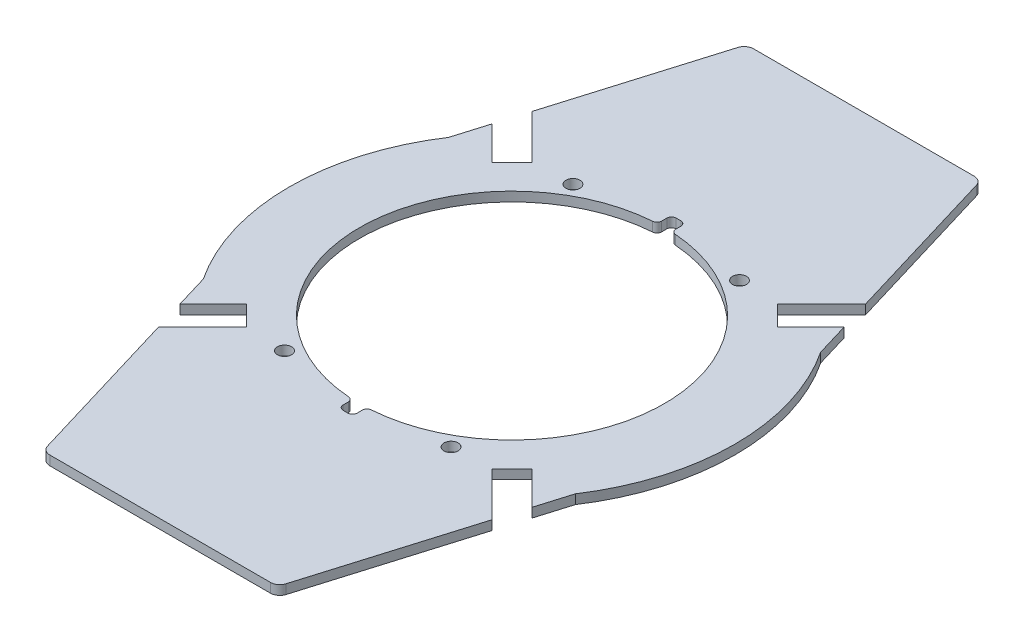
SolidWorks part; units mm, degrees
ref_plane "Front Plane" through (0, 0, 0) normal (0, 0, 1) x (1, 0, 0)
ref_plane "Top Plane" through (0, 0, 0) normal (0, 1, 0) x (1, 0, 0)
ref_plane "Right Plane" through (0, 0, 0) normal (1, 0, 0) x (0, 0, -1)
sketch "Sketch1" plane through (0, 0, 0) normal (0, 1, 0) x (1, 0, 0)
  line L0 (0, 0) -> (0, 663.0376) construction
  line L1 (0, 0) -> (-847.268, 0) construction
  line L2 (-39.656, 26.1468) -> (-25, 75)
  line L3 (-25, 75) -> (25, 75)
  line L5 (-25, -75) -> (25, -75)
  line L7 (-25, 75) -> (25, -75) construction
  line L8 (-25, -75) -> (25, 75) construction
  line L9 (-39.656, -26.1468) -> (-25, -75)
  line L10 (25, 75) -> (39.656, 26.1468)
  line L11 (39.656, -26.1468) -> (25, -75)
  arc A0 (-39.656, 26.1468) -> (-39.656, -26.1468) centre (0, 0) ccw
  circle A1 centre (0, 0) radius 32.5
  arc A2 (39.656, -26.1468) -> (39.656, 26.1468) centre (0, 0) ccw
  dimension "D1" = 95
  dimension "D2" = 65
  dimension "D3" = 50
  dimension "D4" = 150
extrude "Boss-Extrude1" add sketch "Sketch1" along normal blind 2
sketch "Sketch2" plane through (0, 2, 0) normal (0, 1, 0) x (1, 0, 0)
  line L0 (0, 0) -> (0, 83.0531) construction
  line L1 (0, 0) -> (-108.0433, 0) construction
  line L2 (0, 0) -> (-81.7271, 81.7271) construction
  line L3 (41.0122, 36.7696) -> (30.4056, 26.163)
  line L4 (-41.0122, 36.7696) -> (-36.7696, 41.0122)
  line L5 (-30.4056, 26.163) -> (-26.163, 30.4056)
  line L6 (-36.7696, 41.0122) -> (-26.163, 30.4056)
  line L7 (-41.0122, 36.7696) -> (-30.4056, 26.163)
  line L8 (36.7696, 41.0122) -> (41.0122, 36.7696)
  line L9 (36.7696, 41.0122) -> (26.163, 30.4056)
  line L10 (26.163, 30.4056) -> (30.4056, 26.163)
  line L11 (36.7696, -41.0122) -> (26.163, -30.4056)
  line L12 (41.0122, -36.7696) -> (36.7696, -41.0122)
  line L13 (41.0122, -36.7696) -> (30.4056, -26.163)
  line L14 (30.4056, -26.163) -> (26.163, -30.4056)
  line L15 (-41.0122, -36.7696) -> (-30.4056, -26.163)
  line L16 (-36.7696, -41.0122) -> (-41.0122, -36.7696)
  line L17 (-36.7696, -41.0122) -> (-26.163, -30.4056)
  line L18 (-26.163, -30.4056) -> (-30.4056, -26.163)
  point P24 (0, 0)
  dimension "D1" = 45
  dimension "D2" = 40
  dimension "D3" = 15
  dimension "D4" = 6
  dimension "D5" = 4
extrude "Cut-Extrude1" cut sketch "Sketch2" against normal blind 2
sketch "Sketch3" plane through (0, 2, 0) normal (0, 1, 0) x (1, 0, 0)
  line L0 (0, 0) -> (36.2737, 0) construction
  line L1 (-1.5, 35.5) -> (1.5, 35.5)
  line L2 (-1.5, 35.5) -> (-1.5, 29.5)
  line L3 (-1.5, 29.5) -> (1.5, 29.5)
  line L4 (1.5, 35.5) -> (1.5, 29.5)
  line L5 (-1.5, 35.5) -> (1.5, 29.5) construction
  line L6 (-1.5, 29.5) -> (1.5, 35.5) construction
  line L7 (-1.5, -35.5) -> (1.5, -35.5)
  line L8 (1.5, -35.5) -> (1.5, -29.5)
  line L9 (-1.5, -29.5) -> (1.5, -29.5)
  line L10 (-1.5, -35.5) -> (-1.5, -29.5)
  circle A0 centre (0, 0) radius 32.5 construction
  point P0 (0, 32.5)
  dimension "D1" = 3
  dimension "D2" = 6
extrude "Cut-Extrude2" cut sketch "Sketch3" against normal blind 2
fillet "Fillet1" radius 1 8 edges at (-1.5, 1, -32.4654) (1.5, 1, -32.4654) (1.5, 1, -35.5) (-1.5, 1, -35.5) (-1.5, 1, 32.4654) (1.5, 1, 32.4654) (1.5, 1, 35.5) (-1.5, 1, 35.5)
fillet "Fillet2" radius 2 4 edges at (25, 1, 75) (-25, 1, 75) (25, 1, -75) (-25, 1, -75)
sketch "Sketch4" plane through (0, 2, 0) normal (0, 1, 0) x (1, 0, 0)
  line L0 (0, 0) -> (0, 75) construction
  line L1 (23.5119, 75) -> (-23.5119, 75) construction
  line L2 (0, 0) -> (-70.2392, 0) construction
  line L3 (0, 0) -> (-40.7309, 70.548) construction
  circle A0 centre (-17.75, 30.7439) radius 1.5
  circle A1 centre (17.75, 30.7439) radius 1.5
  circle A2 centre (17.75, -30.7439) radius 1.5
  circle A3 centre (-17.75, -30.7439) radius 1.5
  dimension "D2" = 3
  dimension "D3" = 35.5
  dimension "D1" = 30
extrude "Cut-Extrude3" cut sketch "Sketch4" against normal blind 2
